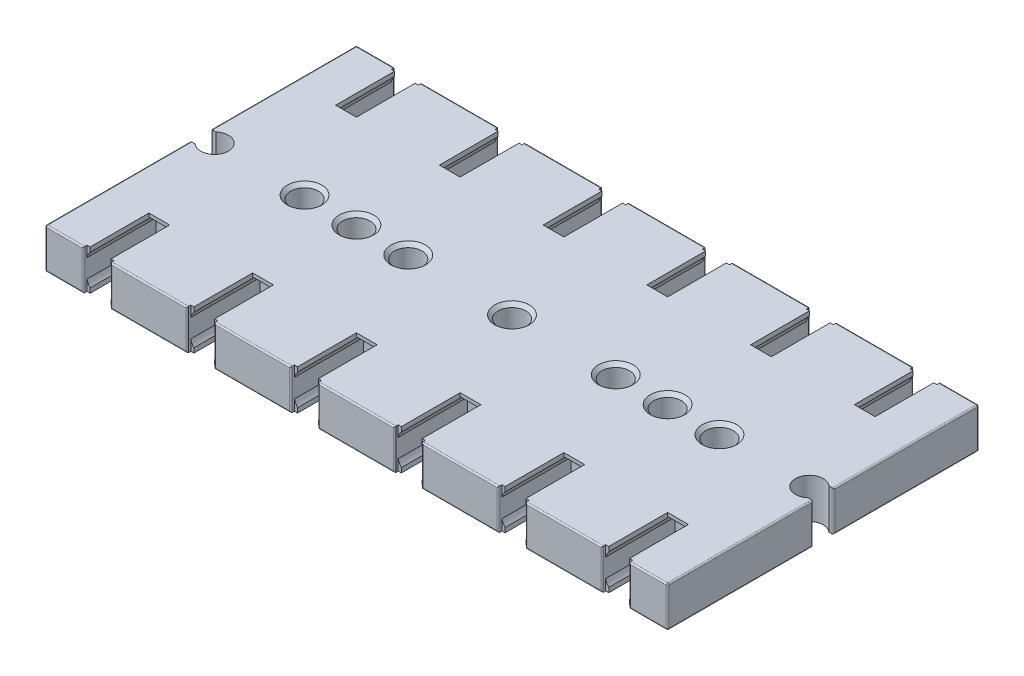
SolidWorks part; units mm, degrees
ref_plane "前视基准面" through (0, 0, 0) normal (0, 0, 1) x (1, 0, 0)
ref_plane "上视基准面" through (0, 0, 0) normal (0, 1, 0) x (1, 0, 0)
ref_plane "右视基准面" through (0, 0, 0) normal (1, 0, 0) x (0, 0, -1)
sketch "草图1" plane through (0, 0, 0) normal (0, 1, 0) x (1, 0, 0)
  line L0 (45, -22.5) -> (45, 22.5)
  line L1 (45, -22.5) -> (-45, -22.5)
  line L2 (45, 22.5) -> (-45, 22.5)
  line L3 (-45, -22.5) -> (-45, 22.5)
  line L4 (45, -22.5) -> (-45, 22.5) construction
  line L5 (45, 22.5) -> (-45, -22.5) construction
  point P1 (0, 0)
  dimension "D1" = 90
  dimension "D2" = 45
extrude "凸台-拉伸1" add sketch "草图1" along normal blind 5.8
sketch "草图2" plane through (0, 0, 22.5) normal (0, 0, 1) x (1, 0, 0)
  line L0 (-45, 5.8) -> (-37.5, 5.8) construction
  line L1 (-45, 5.8) -> (45, 5.8) construction
  line L2 (-37.5, 5.8) -> (-37.5, 3.8) construction
  line L4 (-37.5, 3.8) -> (-37.5, 2) construction
  line L5 (-37.5, 2) -> (-37.5, 0) construction
  line L6 (-45, 0) -> (45, 0) construction
  line L7 (-36, 5.8) -> (-39, 5.8)
  line L8 (-39, 5.8) -> (-39, 5.1229)
  line L9 (-37.5, 3.8) -> (-37.5, 3) construction
  line L11 (-39.45, 3) -> (-39.45, 4.2444)
  line L12 (-35.55, 3) -> (-35.55, 4.2444)
  line L13 (-36, 5.8) -> (-36, 5.1229)
  line L14 (-45, 2.9) -> (-40.7216, 2.9) construction
  line L15 (-45, 5.8) -> (-45, 0) construction
  line L16 (-35.55, 2.8) -> (-35.55, 1.5556)
  line L17 (-39.45, 2.8) -> (-39.45, 1.5556)
  line L18 (-36, 0) -> (-39, 0)
  line L19 (-36, 0) -> (-36, 0.6771)
  line L20 (-39, 0) -> (-39, 0.6771)
  line L21 (-39.45, 3) -> (-39.45, 2.8)
  line L22 (-35.55, 3) -> (-35.55, 2.8)
  arc A0 (-36, 5.1229) -> (-35.55, 4.2444) centre (-37.5, 3.8) cw
  arc A1 (-39, 5.1229) -> (-39.45, 4.2444) centre (-37.5, 3.8) ccw
  arc A2 (-36, 0.6771) -> (-35.55, 1.5556) centre (-37.5, 2) ccw
  arc A3 (-39, 0.6771) -> (-39.45, 1.5556) centre (-37.5, 2) cw
  dimension "D7" = 2
  dimension "D1" = 7.5
  dimension "D2" = 2
  dimension "D4" = 1.5
  dimension "D5" = 0.8
  dimension "D6" = 1.95
extrude "切除-拉伸2" cut sketch "草图2" against normal blind 10.5
sketch "草图3" plane through (0, 0, 22.5) normal (0, 0, 1) x (1, 0, 0)
  line L0 (-45, 2.9) -> (-37.5, 2.9) construction
  line L1 (-45, 5.8) -> (-45, 0) construction
  line L2 (-39.45, 5.8) -> (-39.45, 0)
  line L3 (-39.45, 5.8) -> (-35.55, 5.8)
  line L4 (-39.45, 0) -> (-35.55, 0)
  line L5 (-35.55, 5.8) -> (-35.55, 0)
  line L6 (-39.45, 5.8) -> (-35.55, 0) construction
  line L7 (-39.45, 0) -> (-35.55, 5.8) construction
  dimension "D1" = 7.5
  dimension "D2" = 3.9
  dimension "D3" = 5.8
extrude "切除-拉伸3" cut sketch "草图3" against normal blind 0.5
sketch "草图4" plane through (0, 0, 12) normal (0, 0, 1) x (1, 0, 0)
  line L0 (-39, 5.8) -> (-36, 5.8)
  line L1 (-36, 5.8) -> (-36, 5.3)
  line L2 (-36, 5.1229) -> (-36, 5.8) construction
  line L3 (-36, 5.3) -> (-39, 5.3)
  line L4 (-39, 5.8) -> (-39, 5.1229) construction
  line L5 (-39, 5.3) -> (-39, 5.8)
  line L6 (-39, 0) -> (-36, 0)
  line L7 (-36, 0) -> (-36, 0.5)
  line L8 (-36, 0) -> (-36, 0.6771) construction
  line L9 (-36, 0.5) -> (-39, 0.5)
  line L10 (-39, 0.6771) -> (-39, 0) construction
  line L11 (-39, 0.5) -> (-39, 0)
  dimension "D1" = 0.5
  dimension "D2" = 0.5
extrude "凸台-拉伸2" add sketch "草图4" along normal blind 1.5
mirror "镜向1" about plane through (0, 0, 0) normal (0, 0, 1) of "凸台-拉伸2", "切除-拉伸3", "切除-拉伸2"
pattern_linear "阵列(线性)1" count 6 spacing 15 along (1, 0, 0) of "镜向1", "切除-拉伸2", "切除-拉伸3", "凸台-拉伸2"
sketch "草图5" plane through (0, 5.8, 0) normal (0, 1, 0) x (1, 0, 0)
  circle A0 centre (0, 0) radius 2
  dimension "D1" = 4
extrude "切除-拉伸4" cut sketch "草图5" against normal up to next
pattern_linear "阵列(线性)4" count 3 spacing 15 along (-1, 0, 0) count 3 spacing 15 along (1, 0, 0) of "切除-拉伸4"
sketch "草图6" plane through (0, 5.8, 0) normal (0, 1, 0) x (1, 0, 0)
  line L0 (0, 0) -> (-22.5, 0) construction
  circle A0 centre (-22.5, 0) radius 2
  dimension "D2" = 4
  dimension "D1" = 22.5
extrude "切除-拉伸5" cut sketch "草图6" against normal up to next
mirror "镜向2" about plane through (0, 0, 0) normal (1, 0, 0) of "切除-拉伸5"
sketch "草图7" plane through (0, 5.8, 0) normal (0, 1, 0) x (1, 0, 0)
  line L0 (-45, 0) -> (-43, 0) construction
  line L1 (-45, 22.5) -> (-45, -22.5) construction
  line L2 (-45, -1.5) -> (-45, 1.5)
  line L3 (-45, 1.5) -> (-44.3229, 1.5)
  line L4 (-45, -1.5) -> (-44.3229, -1.5)
  arc A0 (-44.3229, -1.5) -> (-44.3229, 1.5) centre (-43, 0) ccw
  dimension "D3" = 2
  dimension "D1" = 2
  dimension "D2" = 1.5
extrude "切除-拉伸6" cut sketch "草图7" against normal up to next
mirror "镜向3" about plane through (0, 0, 0) normal (1, 0, 0) of "切除-拉伸6"
chamfer "倒角2" distance 0.5 angle 45 14 edges at (30, 0, -2) (30, 5.8, 2) (22.5, 0, -2) (22.5, 5.8, 2) (15, 0, -2) (15, 5.8, 2) (0, 0, -2) (0, 5.8, 2) (-15, 0, -2) (-15, 5.8, 2) (-22.5, 0, -2) (-22.5, 5.8, 2) (-30, 0, -2) (-30, 5.8, 2)
fillet "圆角2" radius 0.2 68 edges at (-42.225, 0, -22.5) (-42.225, 5.8, -22.5) (-39.45, 2.9, -22.5) (-30, 0, -22.5) (-30, 5.8, -22.5) (-35.55, 2.9, -22.5) (-24.45, 2.9, -22.5) (-15, 0, -22.5) (-15, 5.8, -22.5) (-20.55, 2.9, -22.5) (-9.45, 2.9, -22.5) (0, 0, -22.5) (0, 5.8, -22.5) (-5.55, 2.9, -22.5) (5.55, 2.9, -22.5) (15, 0, -22.5) (15, 5.8, -22.5) (9.45, 2.9, -22.5) (20.55, 2.9, -22.5) (30, 0, -22.5) (30, 5.8, -22.5) (24.45, 2.9, -22.5) (35.55, 2.9, -22.5) (42.225, 5.8, -22.5) (42.225, 0, -22.5) (39.45, 2.9, -22.5) (45, 0, -12) (45, 5.8, -12) (45, 2.9, -22.5) (45, 2.9, -1.5) (45, 5.8, 12) (45, 0, 12) (45, 2.9, 1.5) (45, 2.9, 22.5) (42.225, 5.8, 22.5) (42.225, 0, 22.5) (39.45, 2.9, 22.5) (24.45, 2.9, 22.5) (30, 0, 22.5) (30, 5.8, 22.5) (35.55, 2.9, 22.5) (9.45, 2.9, 22.5) (15, 0, 22.5) (15, 5.8, 22.5) (20.55, 2.9, 22.5) (-5.55, 2.9, 22.5) (0, 0, 22.5) (0, 5.8, 22.5) (5.55, 2.9, 22.5) (-20.55, 2.9, 22.5) (-15, 0, 22.5) (-15, 5.8, 22.5) (-9.45, 2.9, 22.5) (-35.55, 2.9, 22.5) (-30, 0, 22.5) (-30, 5.8, 22.5) (-24.45, 2.9, 22.5) (-42.225, 0, 22.5) (-42.225, 5.8, 22.5) (-39.45, 2.9, 22.5) (-45, 2.9, 22.5) (-45, 5.8, 12) (-45, 0, 12) (-45, 2.9, 1.5) (-45, 2.9, -22.5) (-45, 0, -12) (-45, 5.8, -12) (-45, 2.9, -1.5)
